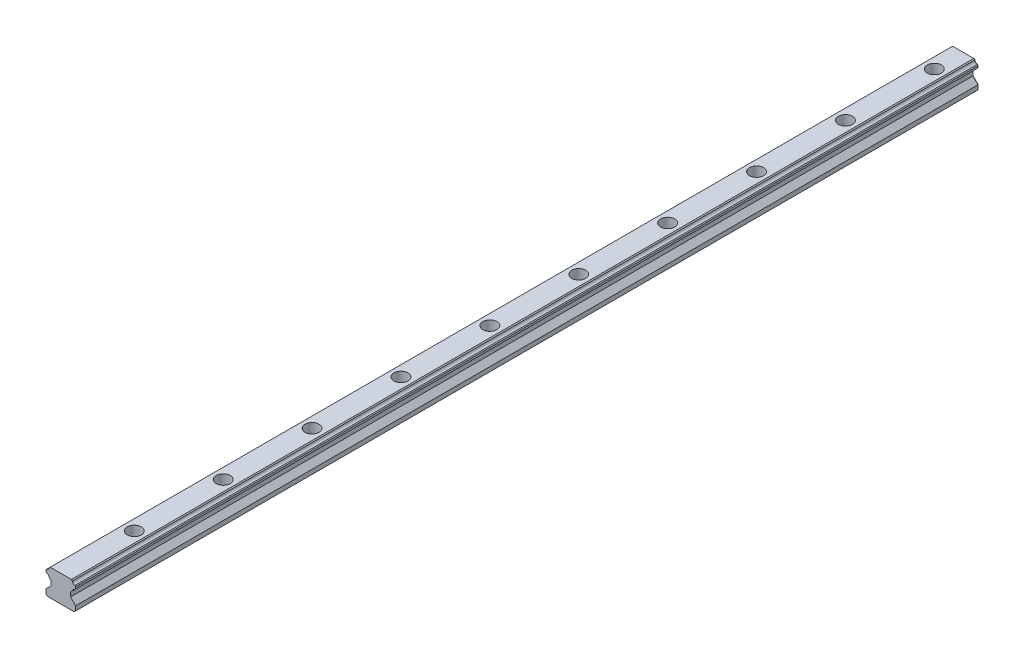
SolidWorks part; units mm, degrees
ref_plane "Front Plane" through (0, 0, 0) normal (0, 0, 1) x (1, 0, 0)
ref_plane "Top Plane" through (0, 0, 0) normal (0, 1, 0) x (1, 0, 0)
ref_plane "Right Plane" through (0, 0, 0) normal (1, 0, 0) x (0, 0, -1)
sketch "Sketch1" plane through (-20, 0, 0) normal (0, 0, 1) x (1, 0, 0)
  line L0 (10, -4.9999) -> (10, -8)
  line L1 (10, -8) -> (11, -9)
  line L2 (11, -9) -> (20, -9)
  line L3 (17, 9) -> (23, 9)
  line L5 (26.55, -1.55) -> (30, -4.9999)
  line L6 (26.55, 1.3792) -> (26.55, -1.55)
  line L7 (27.7679, 2.5951) -> (26.55, 1.3792)
  line L8 (30, 4.8292) -> (29.4727, 4.3144)
  line L9 (30, 6.16) -> (30, 4.8292)
  line L10 (29.4727, 6.6874) -> (30, 6.16)
  line L11 (27.16, 9) -> (27.7679, 8.3921)
  line L13 (29, -9) -> (20, -9)
  line L14 (30, -8) -> (29, -9)
  line L15 (30, -4.9999) -> (30, -8)
  line L16 (27.16, 9) -> (12.84, 9)
  line L17 (12.84, 9) -> (12.2321, 8.3921)
  line L18 (10.5273, 6.6874) -> (10, 6.16)
  line L19 (10, 6.16) -> (10, 4.8292)
  line L20 (10, 4.8292) -> (10.5273, 4.3144)
  line L21 (12.2321, 2.5951) -> (13.45, 1.3792)
  line L22 (13.45, 1.3792) -> (13.45, -1.55)
  line L23 (13.45, -1.55) -> (10, -4.9999)
  line L25 (20, -9) -> (20, 9) construction
  arc A0 (29.4727, 4.3144) -> (27.7679, 2.5951) centre (29.8039, 2.2812) ccw
  arc A1 (27.7679, 8.3921) -> (29.4727, 6.6874) centre (29.8015, 8.7209) ccw
  arc A2 (12.2321, 8.3921) -> (10.5273, 6.6874) centre (10.1985, 8.7209) cw
  arc A3 (10.5273, 4.3144) -> (12.2321, 2.5951) centre (10.1961, 2.2812) cw
  point P3 (20, 0.5)
  point P37 (20, 0)
  point P42 (20, 9)
  dimension "D17" = 2.06
  dimension "Rail Width" = 20
  dimension "D2" = 1
  dimension "D3" = 1
  dimension "D4" = 6
  dimension "D7" = 18
  dimension "D8" = 4.0001
  dimension "D9" = 10.55
  dimension "D10" = 13.1001
  dimension "D11" = 15.5359
  dimension "D12" = 0.6079
  dimension "D13" = 0.6079
  dimension "D15" = 0.5273
  dimension "D16" = 0.5273
  dimension "D18" = 1.2159
  dimension "D19" = 0.5148
  dimension "D20" = 6.4049
  dimension "D21" = 2.84
  dimension "D22" = 4.1708
  dimension "Rail Height" = 18
  dimension "Mounting Hole Dpeth" = 8.5
sketch "Sketch2" plane through (0, 0, 0) normal (1, 0, 0) x (0, 0, -1)
  line L0 (-300, 9) -> (-295.25, 9)
  line L1 (-295.25, 9) -> (-295.25, 0.5)
  line L2 (-295.25, 0.5) -> (-297, 0.5)
  line L3 (-297, 0.5) -> (-297, -9)
  line L4 (-297, -9) -> (-300, -9)
  line L5 (-300, -9) -> (-300, 9) construction
  line L6 (-300, -9) -> (-300, 9) construction
  line L7 (230, 0) -> (-230, 0)
  line L9 (-300, 9) -> (-300, -9)
  line L10 (320, 0) -> (-320, 0) construction
  point P6 (-180, 0)
  point P7 (-300, 0)
  point P8 (-120, 0)
  point P11 (0, 0)
  point P12 (-240, 0)
  point P13 (0, 0)
  point P14 (-230, 0)
  point P18 (60, 0)
  point P21 (0, 0)
  point P22 (230, 0)
  point P24 (-60, 0)
  point P25 (120, 0)
  point P26 (180, 0)
  point P27 (240, 0)
  point P28 (300, 0)
  point P35 (230, -1)
  dimension "D1" = 9.5
  dimension "Rail Length" = 640
  dimension "Mounting Hole Center-to-End" = 20
  dimension "Mounting Hole Center-to-Center" = 60
  dimension "D2" = 90
  dimension "D4" = 1
  dimension "Number of Mounting Holes" = 11
sketch "Sketch3" plane through (0, 0, 0) normal (0, 0, 1) x (1, 0, 0)
  line L0 (-3, 9) -> (3, 9) construction
  line L3 (-3, 9) -> (3, 9)
  line L21 (0, -9) -> (9, -9)
  line L22 (9, -9) -> (10, -8)
  line L23 (10, -8) -> (10, -4.9999)
  line L24 (10, -4.9999) -> (6.55, -1.55)
  line L25 (6.55, -1.55) -> (6.55, 1.3792)
  line L26 (6.55, 1.3792) -> (7.7679, 2.5951)
  line L27 (9.4727, 4.3144) -> (10, 4.8292)
  line L28 (10, 4.8292) -> (10, 6.16)
  line L29 (10, 6.16) -> (9.4727, 6.6874)
  line L30 (7.7679, 8.3921) -> (7.16, 9)
  line L31 (7.16, 9) -> (-7.16, 9)
  line L32 (-7.16, 9) -> (-7.7679, 8.3921)
  line L33 (-9.4727, 6.6874) -> (-10, 6.16)
  line L34 (-10, 6.16) -> (-10, 4.8292)
  line L35 (-10, 4.8292) -> (-9.4727, 4.3144)
  line L36 (-7.7679, 2.5951) -> (-6.55, 1.3792)
  line L37 (-6.55, 1.3792) -> (-6.55, -1.55)
  line L38 (-6.55, -1.55) -> (-10, -4.9999)
  line L39 (-10, -4.9999) -> (-10, -8)
  line L40 (-10, -8) -> (-9, -9)
  line L41 (-9, -9) -> (0, -9)
  line L42 (0, -9) -> (9, -9)
  line L43 (9, -9) -> (10, -8)
  line L44 (10, -8) -> (10, -4.9999)
  line L45 (10, -4.9999) -> (6.55, -1.55)
  line L46 (6.55, -1.55) -> (6.55, 1.3792)
  line L47 (6.55, 1.3792) -> (7.7679, 2.5951)
  line L48 (9.4727, 4.3144) -> (10, 4.8292)
  line L49 (10, 4.8292) -> (10, 6.16)
  line L50 (10, 6.16) -> (9.4727, 6.6874)
  line L51 (7.7679, 8.3921) -> (7.16, 9)
  line L52 (7.16, 9) -> (-7.16, 9)
  line L53 (-7.16, 9) -> (-7.7679, 8.3921)
  line L54 (-9.4727, 6.6874) -> (-10, 6.16)
  line L55 (-10, 6.16) -> (-10, 4.8292)
  line L56 (-10, 4.8292) -> (-9.4727, 4.3144)
  line L57 (-7.7679, 2.5951) -> (-6.55, 1.3792)
  line L58 (-6.55, 1.3792) -> (-6.55, -1.55)
  line L59 (-6.55, -1.55) -> (-10, -4.9999)
  line L60 (-10, -4.9999) -> (-10, -8)
  line L61 (-10, -8) -> (-9, -9)
  line L62 (-9, -9) -> (0, -9)
  arc A4 (9.4727, 4.3144) -> (7.7679, 2.5951) centre (9.8039, 2.2812) ccw
  arc A5 (7.7679, 8.3921) -> (9.4727, 6.6874) centre (9.8015, 8.7209) ccw
  arc A6 (-9.4727, 6.6874) -> (-7.7679, 8.3921) centre (-9.8015, 8.7209) ccw
  arc A7 (-7.7679, 2.5951) -> (-9.4727, 4.3144) centre (-9.8039, 2.2812) ccw
  arc A8 (9.4727, 4.3144) -> (7.7679, 2.5951) centre (9.8039, 2.2812) ccw
  arc A9 (7.7679, 8.3921) -> (9.4727, 6.6874) centre (9.8015, 8.7209) ccw
  arc A10 (-9.4727, 6.6874) -> (-7.7679, 8.3921) centre (-9.8015, 8.7209) ccw
  arc A11 (-7.7679, 2.5951) -> (-9.4727, 4.3144) centre (-9.8039, 2.2812) ccw
  dimension "D1" = 0
extrude "Boss-Extrude1" add sketch "Sketch3" along normal up to vertex (320 mm away) and the other way up to vertex (320 mm away) contours A11 L57 L58 L59 L60 L61 L62 L42 L43 L44 L45 L46 L47 A8 L48 L49 L50 A9 L51 L52 L3 L53 A10 L54 L55 L56 up to point (0, 0, 320) other way up to point (0, 0, -320)
sketch "Sketch4" plane through (0, 0, 0) normal (1, 0, 0) x (0, 0, -1)
  line L6 (-295.25, 9) -> (-300, 9)
  line L7 (-295.25, 0.5) -> (-295.25, 9)
  line L8 (-297, 0.5) -> (-295.25, 0.5)
  line L9 (-297, -9) -> (-297, 0.5)
  line L10 (-300, -9) -> (-297, -9)
  line L11 (-300, 9) -> (-300, -9)
  line L12 (-295.25, 9) -> (-300, 9)
  line L13 (-295.25, 0.5) -> (-295.25, 9)
  line L14 (-297, 0.5) -> (-295.25, 0.5)
  line L15 (-297, -9) -> (-297, 0.5)
  line L16 (-300, -9) -> (-297, -9)
  line L17 (-300, 9) -> (-300, -9)
  dimension "D1" = 0
revolve "Cut-Revolve1" cut sketch "Sketch4" angle 360 about L17
pattern_linear "LPattern2" count 11 spacing 60 along (0, 0, -1) of "Cut-Revolve1"
sketch "Sketch5" plane through (0, 0, 0) normal (0, 1, 0) x (1, 0, 0)
  line L0 (3, -300) -> (0, -300) construction
  line L1 (0, -300) -> (2.1213, -297.8787) construction
  circle A1 centre (0, -300) radius 3 construction
  circle A2 centre (0, -300) radius 3 construction
  point P3 (0, -303)
  point P4 (-3, -300)
  point P6 (3, -300)
  point P7 (2.1213, -297.8787)
  dimension "D1" = 45
sketch "Sketch6" plane through (0, 0, 0) normal (0, 0, 1) x (1, 0, 0)
  line L0 (4.75, 9) -> (-4.75, 9) construction
  line L1 (3, 0.5) -> (-3, 0.5) construction
  line L2 (4.75, 9) -> (-4.75, 9) construction
  line L3 (3, 0.5) -> (-3, 0.5) construction
  line L4 (-4.75, 9) -> (-4.75, 0.5)
  line L5 (-4.75, 0.5) -> (-3, 0.5)
  line L6 (4.75, 9) -> (4.75, 0.5)
  line L7 (4.75, 0.5) -> (3, 0.5)
  line L8 (3, 0.5) -> (3, -9)
  line L9 (-9, -9) -> (9, -9) construction
  line L10 (-3, 0.5) -> (-3, -9)
chamfer "Chamfer1" distance 0.5 angle 45 48 edges at (-7.159, 1.9872, -320) (-6.55, -0.0854, -320) (-8.275, -3.275, -320) (-10, -6.5, -320) (-9.5, -8.5, -320) (0, -9, -320) (9.5, -8.5, -320) (10, -6.5, -320) (8.275, -3.275, -320) (6.55, -0.0854, -320) (7.159, 1.9872, -320) (8.3411, 3.7316, -320) (9.7363, 4.5718, -320) (10, 5.4946, -320) (9.7363, 6.4237, -320) (8.3449, 7.2643, -320) (7.464, 8.6961, -320) (0, 9, -320) (-7.464, 8.6961, -320) (-8.3449, 7.2643, -320) (-9.7363, 6.4237, -320) (-10, 5.4946, -320) (-9.7363, 4.5718, -320) (-8.3411, 3.7316, -320) (-9.7363, 4.5718, 320) (-10, 5.4946, 320) (-9.7363, 6.4237, 320) (-8.3449, 7.2643, 320) (-7.464, 8.6961, 320) (0, 9, 320) (7.464, 8.6961, 320) (8.3449, 7.2643, 320) (9.7363, 6.4237, 320) (10, 5.4946, 320) (9.7363, 4.5718, 320) (8.3411, 3.7316, 320) (7.159, 1.9872, 320) (6.55, -0.0854, 320) (8.275, -3.275, 320) (10, -6.5, 320) (9.5, -8.5, 320) (0, -9, 320) (-9.5, -8.5, 320) (-10, -6.5, 320) (-8.275, -3.275, 320) (-6.55, -0.0854, 320) (-7.159, 1.9872, 320) (-8.3411, 3.7316, 320)
sketch "Sketch7" plane through (0, -9, 0) normal (0, -1, 0) x (1, 0, 0)
  line L0 (23.9249, 289.6) -> (-18.5415, 289.6)
  line L2 (8.7929, -320) -> (-8.7929, -320) construction
  dimension "D1" = 609.6
extrude "Cut-Extrude1" cut sketch "Sketch7" against normal through all and the other way through all flip side to cut
equation "\"D3@LPattern2\"=\"Mounting Hole Center-to-Center@Sketch2\""
equation "\"D1@LPattern2\"=\"Number of Mounting Holes@Sketch2\""
